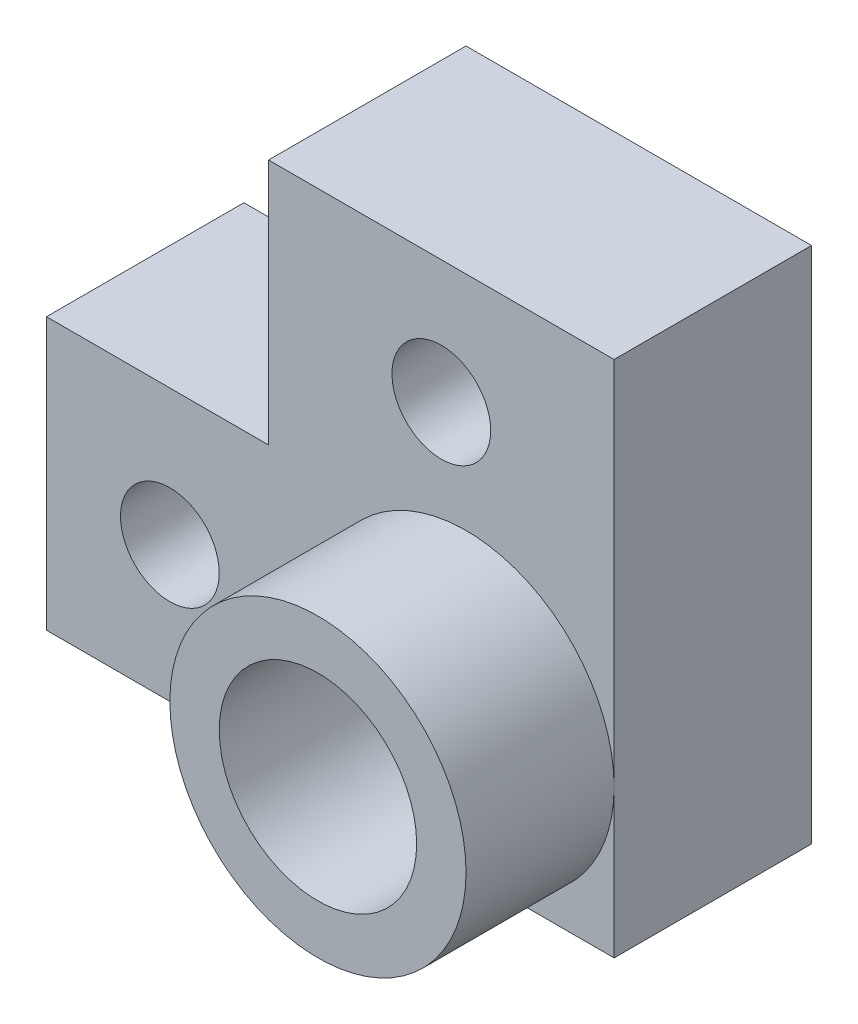
SolidWorks part; units mm, degrees
material "ABS"
ref_plane "Front Plane" through (0, 0, 0) normal (0, 0, 1) x (1, 0, 0)
ref_plane "Top Plane" through (0, 0, 0) normal (0, 1, 0) x (1, 0, 0)
ref_plane "Right Plane" through (0, 0, 0) normal (1, 0, 0) x (0, 0, -1)
sketch "Sketch1" plane through (0, 0, 0) normal (0, 0, 1) x (1, 0, 0)
  line L1 (-12.7947, 11.9139) -> (10.2053, 11.9139)
  line L2 (-12.7947, 11.9139) -> (-12.7947, 0.9139)
  line L3 (-12.7947, 0.9139) -> (10.2053, 0.9139)
  line L4 (10.2053, 11.9139) -> (10.2053, 0.9139)
  dimension "D1" = 11
  dimension "D2" = 23
extrude "Boss-Extrude1" add sketch "Sketch1" along normal blind 8
sketch "Sketch2" plane through (0, 11.9139, 0) normal (0, 1, 0) x (1, 0, 0)
  line L0 (10.2053, 0) -> (-12.7947, 0) construction
  line L1 (10.2053, -8) -> (-3.7947, -8)
  line L2 (10.2053, -8) -> (10.2053, 0)
  line L3 (10.2053, 0) -> (-3.7947, 0)
  line L4 (-3.7947, -8) -> (-3.7947, 0)
  dimension "D1" = 14
extrude "Boss-Extrude2" add sketch "Sketch2" along normal blind 10
sketch "Sketch3" plane through (0, 0, 8) normal (0, 0, 1) x (1, 0, 0)
  line L0 (-3.7947, 11.9139) -> (-12.7947, 11.9139) construction
  line L1 (10.2053, 0.9139) -> (10.2053, 21.9139) construction
  line L2 (-3.7947, 21.9139) -> (10.2053, 21.9139) construction
  line L3 (-12.7947, 11.9139) -> (-12.7947, 0.9139) construction
  circle A0 centre (-7.7947, 6.4139) radius 2
  circle A1 centre (3.2053, 16.9139) radius 2
  dimension "D1" = 4
  dimension "D2" = 4
  dimension "D3" = 5.5
  dimension "D4" = 7
  dimension "D5" = 5
  dimension "D6" = 5
extrude "Cut-Extrude1" cut sketch "Sketch3" against normal blind 20
sketch "Sketch4" plane through (0, 0, 8) normal (0, 0, 1) x (1, 0, 0)
  line L0 (10.2053, 0.9139) -> (10.2053, 21.9139) construction
  line L1 (-12.7947, 0.9139) -> (10.2053, 0.9139) construction
  circle A0 centre (4.2053, 6.9139) radius 4
  dimension "D1" = 8
  dimension "D2" = 6
  dimension "D3" = 6
extrude "Cut-Extrude2" cut sketch "Sketch4" against normal blind 20
sketch "Sketch5" plane through (0, 0, 8) normal (0, 0, 1) x (1, 0, 0)
  circle A0 centre (4.2053, 6.9139) radius 6
  circle A1 centre (4.2053, 6.9139) radius 4
  dimension "D1" = 12
extrude "Boss-Extrude3" add sketch "Sketch5" along normal blind 6
